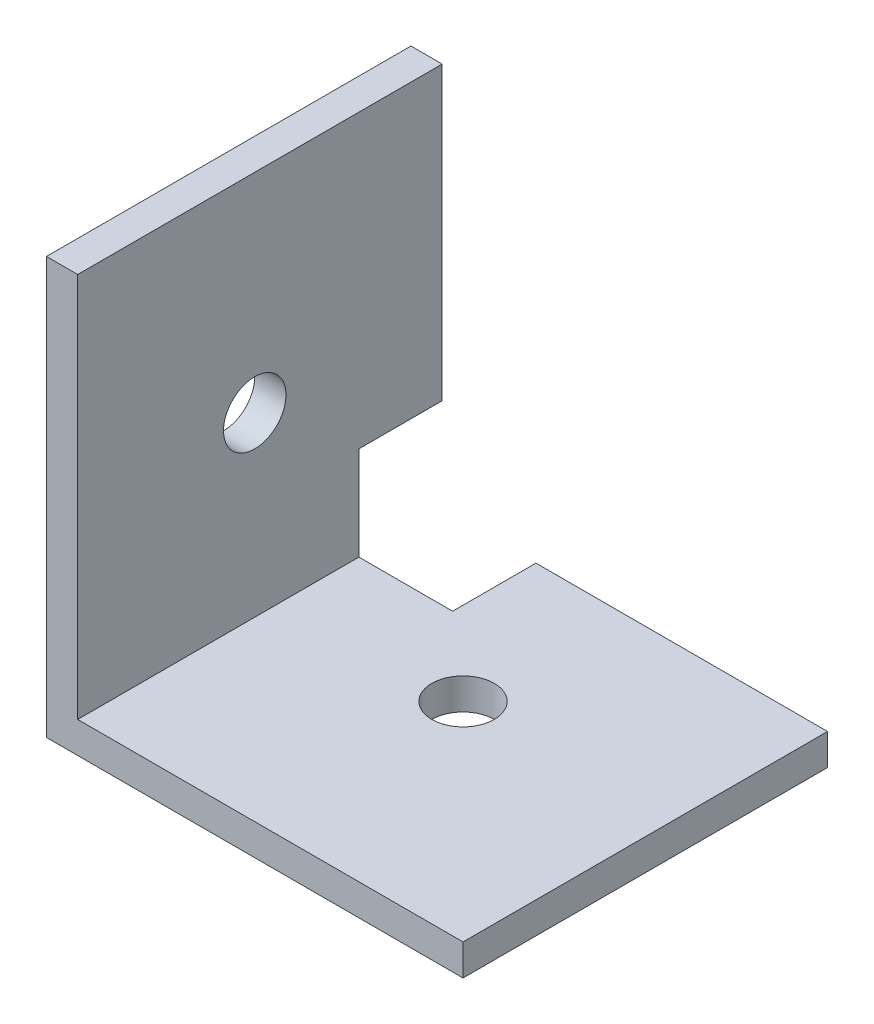
SolidWorks part; units mm, degrees
ref_plane "Plan de face" through (0, 0, 0) normal (0, 0, 1) x (1, 0, 0)
ref_plane "Plan de dessus" through (0, 0, 0) normal (0, 1, 0) x (1, 0, 0)
ref_plane "Plan de droite" through (0, 0, 0) normal (1, 0, 0) x (0, 0, -1)
sketch "Esquisse1" plane through (0, 0, 0) normal (0, 0, 1) x (1, 0, 0)
  line L0 (0, 0) -> (20, 0)
  line L1 (20, 0) -> (20, 1.5)
  line L2 (20, 1.5) -> (1.5, 1.5)
  line L3 (1.5, 1.5) -> (1.5, 20)
  line L4 (1.5, 20) -> (0, 20)
  line L5 (0, 20) -> (0, 0)
  dimension "D1" = 1.5
  dimension "D2" = 1.5
  dimension "D3" = 20
  dimension "D4" = 20
extrude "Extrusion1" add sketch "Esquisse1" along normal blind 17.5
sketch "Esquisse7" plane through (0, 1.5, 0) normal (0, 1, 0) x (-1, 0, 0)
  line L0 (-20, 17.5) -> (-20, 0) construction
  line L1 (-20, 17.5) -> (-1.5, 17.5) construction
  circle A0 centre (-10, 7.5) radius 1.5
  dimension "D1" = 10
  dimension "D2" = 10
extrude "Extrusion7" cut sketch "Esquisse7" against normal through all
sketch "Esquisse9" plane through (1.5, 0, 0) normal (1, 0, 0) x (0, 0, -1)
  line L0 (-17.5, 1.5) -> (-17.5, 20) construction
  line L1 (-17.5, 20) -> (0, 20) construction
  circle A0 centre (-9, 10) radius 1.5
  dimension "D1" = 8.5
  dimension "D3" = 10
extrude "Extrusion8" cut sketch "Esquisse9" against normal through all
sketch "Esquisse10" plane through (0, 0, 0) normal (-1, 0, 0) x (0, 0, 1)
  line L1 (0, 0) -> (4, 0)
  line L2 (0, 0) -> (0, 6)
  line L3 (0, 6) -> (4, 6)
  line L4 (4, 0) -> (4, 6)
  dimension "D1" = 6
  dimension "D2" = 4
extrude "Extrusion9" cut sketch "Esquisse10" against normal blind 6
